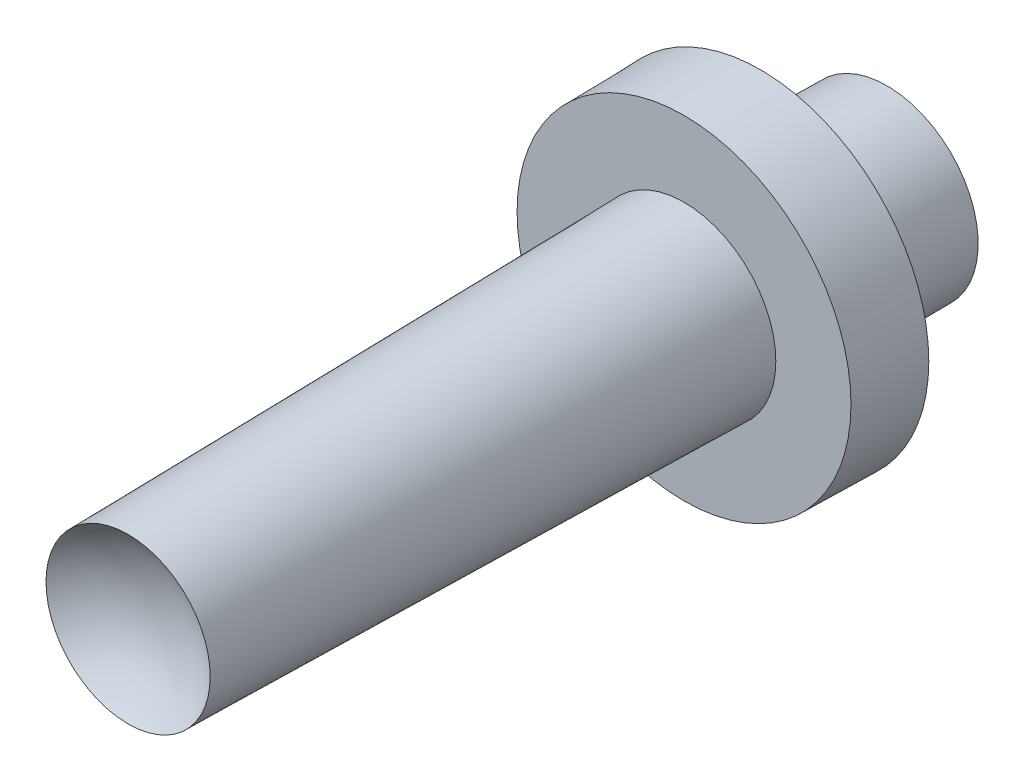
SolidWorks part; units mm, degrees
ref_plane "Front" through (0, 0, 0) normal (0, 0, 1) x (1, 0, 0)
ref_plane "Top" through (0, 0, 0) normal (0, 1, 0) x (1, 0, 0)
ref_plane "Right" through (0, 0, 0) normal (1, 0, 0) x (0, 0, -1)
sketch "Sketch1" plane through (0, 0, 0) normal (0, 0, 1) x (1, 0, 0)
  circle A0 centre (0, 0) radius 2.794
  dimension "D1" = 5.588
extrude "Boss-Extrude1" add sketch "Sketch1" along normal blind 1.27 draft 1
sketch "Sketch2" plane through (0, 0, 1.27) normal (0, 0, 1) x (1, 0, 0)
  circle A0 centre (0, 0) radius 1.524
  dimension "D1" = 3.048
extrude "Boss-Extrude2" add sketch "Sketch2" along normal blind 9.23 draft 1
sketch "Sketch3" plane through (0, 0, 0) normal (0, 0, -1) x (-1, 0, 0)
  circle A0 centre (0, 0) radius 1.55
  dimension "D1" = 3.1
extrude "Boss-Extrude3" add sketch "Sketch3" along normal blind 2.1 draft 1
ref_axis "Axis1" through (0, 0, 1.27) along (0, 0, 1)
ref_plane "Plane1" through (0, 0, 0) normal (0, 1, 0) x (1, 0, 0)
sketch "Sketch5" plane through (0, 0, 0) normal (0, 1, 0) x (1, 0, 0)
  line L0 (0, -10.5) -> (0, -9.9412)
  line L1 (1.3629, -10.5) -> (1.3629, -10.8239)
  line L2 (0, -9.9412) -> (-0.3156, -9.9412) construction
  line L3 (1.3629, -10.8239) -> (0, -10.8239)
  line L4 (0, -10.8239) -> (0, -10.5)
  line L5 (-1.3629, -10.5) -> (1.3629, -10.5) construction
  arc A0 (0, -9.9412) -> (1.3629, -10.5) centre (0, -11.8826) cw
  dimension "D1" = 0.5588
  dimension "D2" = 0.3239
revolve "Cut-Revolve4" cut sketch "Sketch5" angle 360 about axis through (0, 0, 1.27) along (0, 0, 1)
